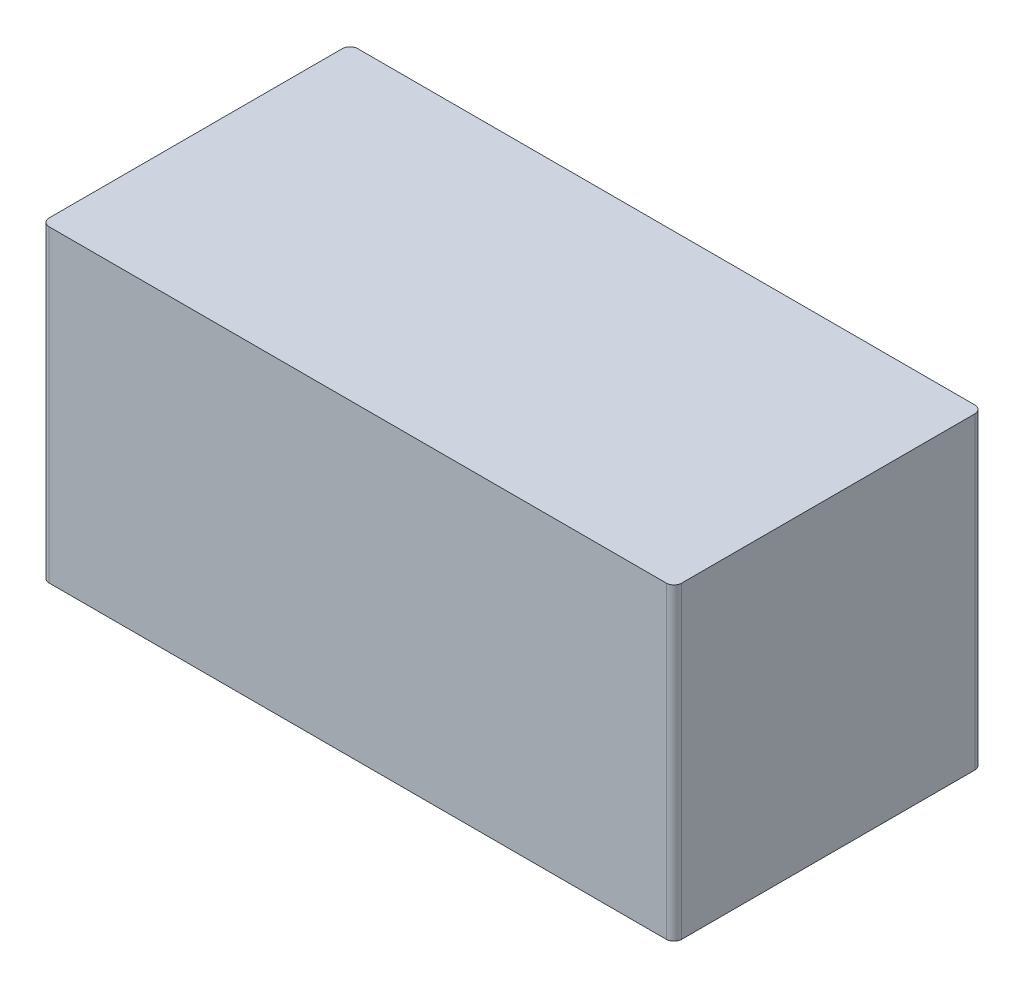
SolidWorks part; units mm, degrees
ref_plane "Front Plane" through (0, 0, 0) normal (0, 0, 1) x (1, 0, 0)
ref_plane "Top Plane" through (0, 0, 0) normal (0, 1, 0) x (1, 0, 0)
ref_plane "Right Plane" through (0, 0, 0) normal (1, 0, 0) x (0, 0, -1)
sketch "Sketch1" plane through (0, 0, 0) normal (0, 1, 0) x (1, 0, 0)
  line L0 (0, 0) -> (41, 0)
  line L1 (41, 0) -> (41, 20)
  line L2 (41, 20) -> (0, 20)
  line L3 (0, 20) -> (0, 0)
extrude "Boss-Extrude1" add sketch "Sketch1" along normal blind 20
fillet "Fillet1" radius 0.5 4 edges at (0, 10, -20) (0, 10, 0) (41, 10, -20) (41, 10, 0)
